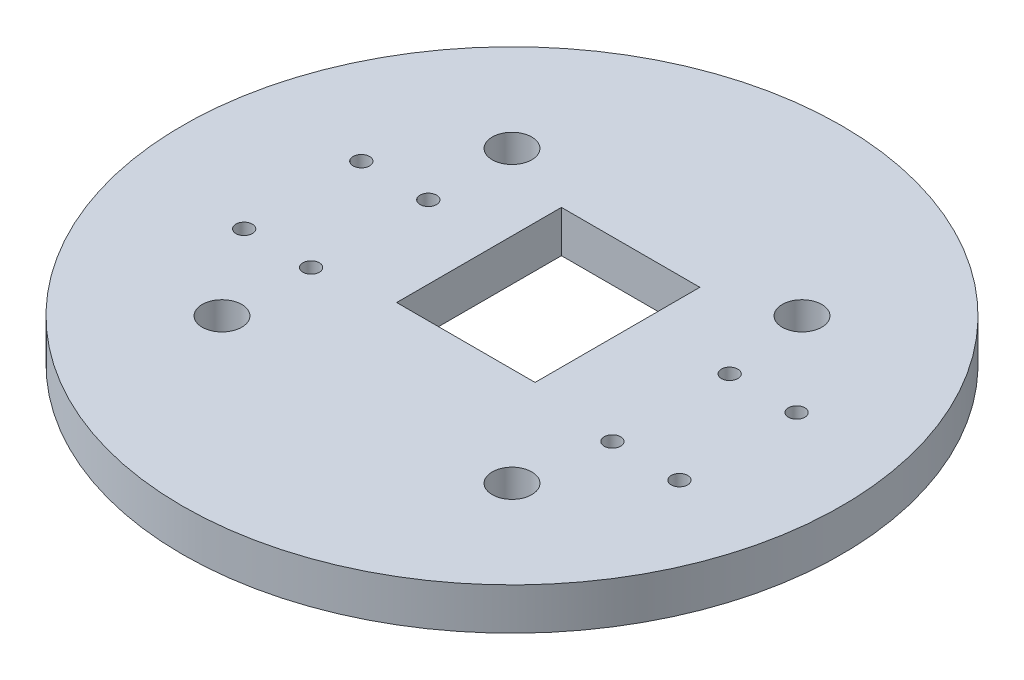
SolidWorks part; units mm, degrees
ref_plane "Front Plane" through (0, 0, 0) normal (0, 0, 1) x (1, 0, 0)
ref_plane "Top Plane" through (0, 0, 0) normal (0, 1, 0) x (1, 0, 0)
ref_plane "Right Plane" through (0, 0, 0) normal (1, 0, 0) x (0, 0, -1)
sketch "Sketch1" plane through (0, 0, 0) normal (0, 1, 0) x (1, 0, 0)
  line L0 (-22, -22) -> (22, 22) construction
  line L1 (-22, -22) -> (-22, 22) construction
  line L2 (-22, 0) -> (22, 0) construction
  line L3 (-22, -22) -> (22, -22) construction
  line L4 (22, -22) -> (22, 22) construction
  line L5 (-22, 22) -> (22, 22) construction
  line L6 (-22, 22) -> (22, -22) construction
  line L7 (0, -22) -> (0, 22) construction
  line L9 (-10.5, -7) -> (10.5, -7)
  line L10 (-10.5, -7) -> (-10.5, 18)
  line L11 (-10.5, 18) -> (10.5, 18)
  line L12 (10.5, -7) -> (10.5, 18)
  circle A0 centre (22, 22) radius 3
  circle A1 centre (-22, 22) radius 3
  circle A2 centre (-22, -22) radius 3
  circle A3 centre (22, -22) radius 3
  circle A4 centre (0, 0) radius 50
  dimension "D2" = 6
  dimension "D3" = 100
  dimension "D4" = 25
  dimension "D1" = 44
  dimension "D6" = 21
  dimension "D7" = 18
extrude "Boss-Extrude1" add sketch "Sketch1" along normal blind 6.35
sketch "Sketch2" plane through (0, 6.35, 0) normal (0, 1, 0) x (1, 0, 0)
  circle A0 centre (22, 22) radius 3 construction
  circle A1 centre (22.225, -22.225) radius 5
  circle A2 centre (22.225, -22.225) radius 3
  circle A3 centre (22, 22) radius 3
  circle A4 centre (22, 22) radius 5
  circle A5 centre (-22, -22.45) radius 5
  circle A6 centre (-22, -22.45) radius 3
  circle A7 centre (-22.225, 21.775) radius 5
  circle A8 centre (-22.225, 21.775) radius 3
  point P20 (0, -0.225)
  dimension "D1" = 4
  dimension "D2" = 2
extrude "Boss-Extrude2" [suppressed] add sketch "Sketch2" along normal blind 19.5
ref_plane "Plane1" [suppressed] through (0, 14.75, 0) normal (0, 1, 0) x (1, 0, 0)
mirror "Mirror1" [suppressed] about plane through (0, 14.75, 0) normal (0, 1, 0)
hole_wizard "M3x0.5 Tapped Hole1" positions "Sketch4" profile "Sketch3" tap size "M3x0.5" standard "ANSI Metric" end condition through all
sketch "Sketch4" plane through (0, 0, 0) normal (0, -1, 0) x (-1, 0, 0)
  line L3 (50, 0) -> (-50, 0) construction
  line L5 (0, 50) -> (0, -50) construction
  line L8 (50, 50) -> (-50, 50) construction
  line L9 (-50, 50) -> (-50, -50) construction
  line L10 (-50, -50) -> (50, -50) construction
  line L12 (50, 50) -> (50, -50) construction
  line L14 (13.97, -26.67) -> (-13.97, -26.67)
  line L16 (13.97, -26.67) -> (13.97, -13.97)
  line L18 (-13.97, -26.67) -> (-13.97, -13.97)
  line L20 (-13.97, -13.97) -> (-29.21, -13.97)
  line L21 (-29.21, -13.97) -> (-29.21, 13.97)
  line L22 (-29.21, 13.97) -> (-13.97, 13.97)
  line L23 (-13.97, 13.97) -> (-13.97, 36.83)
  line L24 (-13.97, 36.83) -> (13.97, 36.83)
  line L25 (13.97, 36.83) -> (13.97, 13.97)
  line L26 (13.97, 13.97) -> (26.67, 13.97)
  line L27 (26.67, 13.97) -> (26.67, -13.97)
  line L28 (26.67, -13.97) -> (13.97, -13.97)
  line L30 (49.2033, 8.89) -> (-49.2033, 8.89) construction
  circle A0 centre (0, 0) radius 50 construction
  point P96 (21.59, 8.89)
  point P100 (-24.13, 8.89)
  point P103 (-24.13, -8.89)
  point P104 (21.59, -8.89)
  point P105 (31.75, 8.89)
  point P107 (-34.29, 8.89)
  point P120 (31.75, -8.89)
  point P121 (-34.29, -8.89)
  dimension "D1" = 27.94
  dimension "D2" = 12.7
  dimension "D3" = 15.24
  dimension "D4" = 12.7
  dimension "D5" = 22.86
  dimension "D6" = 21.59
  dimension "D7" = 8.89
  dimension "D8" = 24.13
  dimension "D10" = 5.08
  dimension "D11" = 5.08
sketch "Sketch3" plane through (-21.59, 0, -8.89) normal (1, 0, 0) x (0, 0, -1)
  line L0 (0, 0) -> (0, 6.35)
  line L1 (0, 6.35) -> (1.25, 6.35)
  line L2 (1.25, 6.35) -> (1.25, 0)
  line L5 (1.25, 0) -> (0, 0)
  line L11 (0, -6.35) -> (0, 107.95) construction
  dimension "Thread Major Dia." = 2.5
  dimension "Thru Tap Drill Depth" = 6.35
